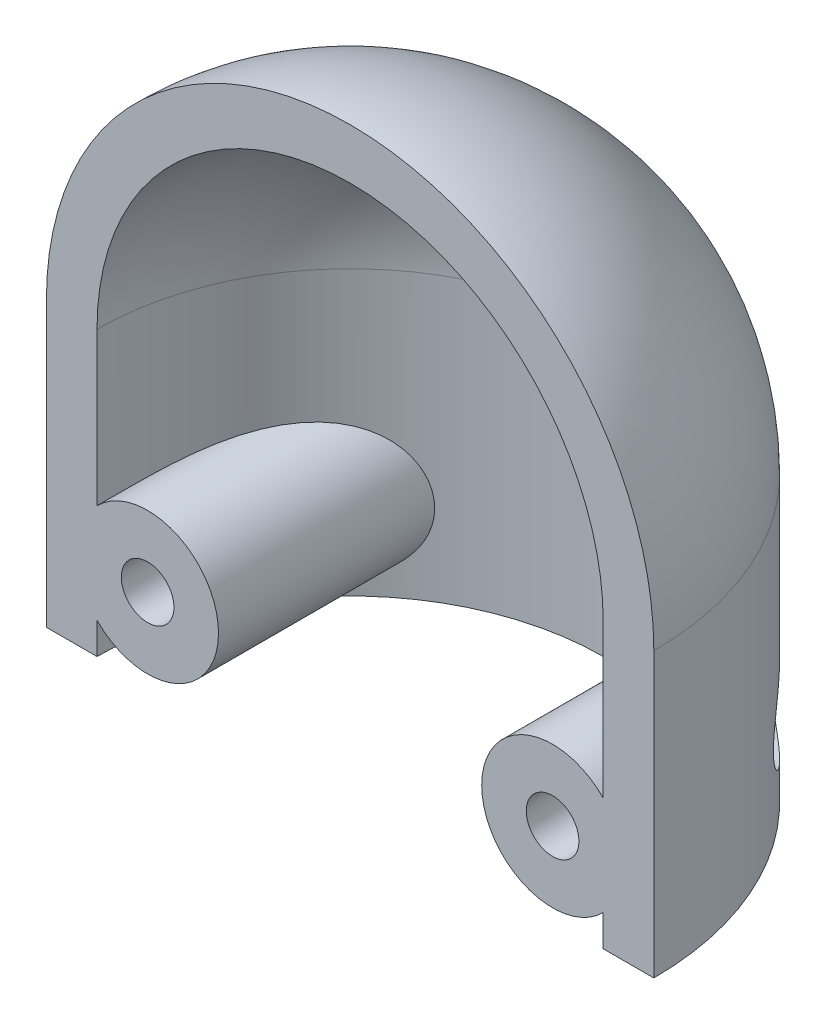
SolidWorks part; units mm, degrees
ref_plane "Ebene vorne" through (0, 0, 0) normal (0, 0, 1) x (1, 0, 0)
ref_plane "Ebene oben" through (0, 0, 0) normal (0, 1, 0) x (1, 0, 0)
ref_plane "Ebene rechts" through (0, 0, 0) normal (1, 0, 0) x (0, 0, -1)
sketch "Skizze1" plane through (0, 0, 0) normal (0, 0, 1) x (1, 0, 0)
  line L0 (0, 26.5) -> (0, 24)
  line L1 (-12.5, 3.1583) -> (-12.5, -0.1583)
  line L16 (-15, 11.5) -> (-15, -2.5)
  line L17 (-15, -2.5) -> (-12.5, -2.5)
  line L18 (-12.5, -2.5) -> (-12.5, -0.1583)
  line L19 (-12.5, 3.1583) -> (-12.5, 11.5)
  arc A8 (0, 26.5) -> (-15, 11.5) centre (0, 11.5) ccw
  arc A10 (0, 24) -> (-12.5, 11.5) centre (0, 11.5) ccw
revolve "Rotation1" add sketch "Skizze1" angle 180 about L0
sketch "Skizze2" plane through (0, 0, 0) normal (0, 0, 1) x (1, 0, 0)
  line L0 (-12.5, 3.1583) -> (-12.5, -0.1583)
  circle A0 centre (-10, 1.5) radius 3.5
  arc A9 (-12.5, -0.1583) -> (-12.5, 3.1583) centre (-10, 1.5) ccw
  dimension "D1" = 7
extrude "Aufsatz-Linear austragen1" add sketch "Skizze2" against normal up to surface (10.6771 mm away) contours L0 A9 | A0 A9 L0
sketch "Skizze4" plane through (0, 0, 0) normal (0, 0, 1) x (1, 0, 0)
  circle A0 centre (-10, 1.5) radius 1.3
  dimension "D1" = 2.6
extrude "Schnitt-Linear austragen1" cut sketch "Skizze4" against normal through all
sketch "Skizze5" plane through (0, 0, 0) normal (0, 0, 1) x (1, 0, 0)
  circle A0 centre (-10, 1.5) radius 2.25
  dimension "D1" = 4.5
extrude "Schnitt-Linear austragen2" cut sketch "Skizze5" against normal through all from offset 2 offset against normal yes
mirror "Spiegeln1" about plane through (0, 0, 0) normal (1, 0, 0) of "Schnitt-Linear austragen2", "Aufsatz-Linear austragen1", "Schnitt-Linear austragen1"
